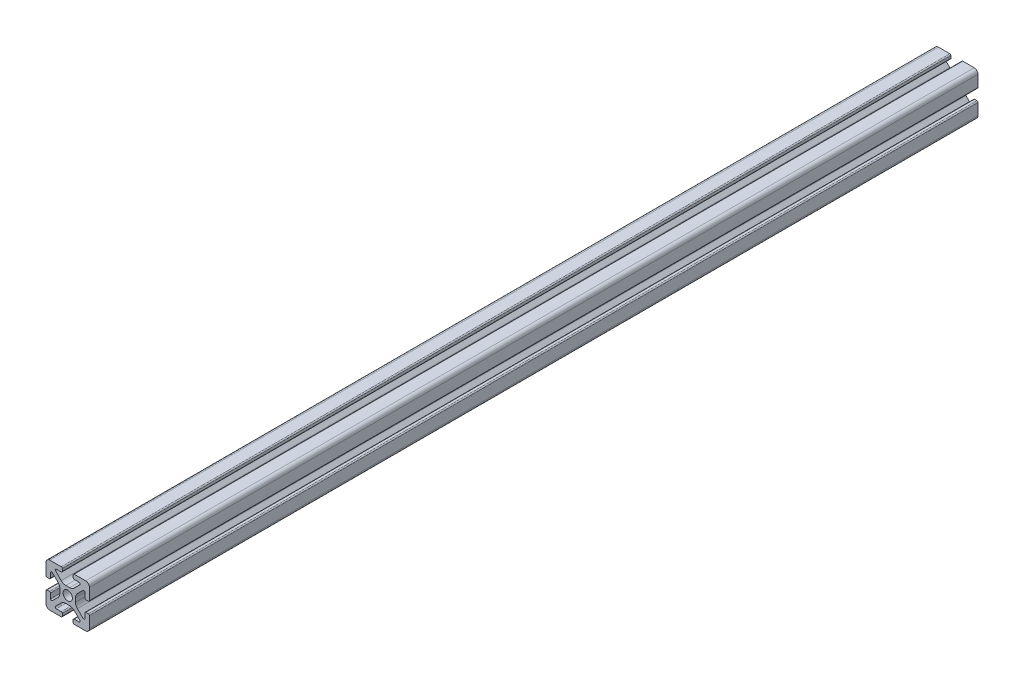
SolidWorks part; units mm, degrees
ref_plane "Front Plane" through (0, 0, 0) normal (0, 0, 1) x (1, 0, 0)
ref_plane "Top Plane" through (0, 0, 0) normal (0, 1, 0) x (1, 0, 0)
ref_plane "Right Plane" through (0, 0, 0) normal (1, 0, 0) x (0, 0, -1)
sketch "Sketch2" plane through (0, 0, 0) normal (0, 0, 1) x (1, 0, 0)
  line L0 (0, 10) -> (0, -10) construction
  line L1 (-10, 0) -> (10, 0) construction
  line L2 (2.5, -10) -> (10, -10)
  line L3 (10, -10) -> (10, -2.5)
  line L4 (2.5, -10) -> (2.5, -7.9246)
  line L5 (2.5, -7.9246) -> (6.4571, -7.9246)
  line L6 (6.4571, -7.9246) -> (2.1325, -3.6)
  line L7 (0, 0) -> (10, -10) construction
  line L8 (10, -2.5) -> (7.9246, -2.5)
  line L9 (7.9246, -2.5) -> (7.9246, -6.4571)
  line L10 (7.9246, -6.4571) -> (3.6, -2.1325)
  line L11 (5.7623, -4.2948) -> (4.2948, -5.7623) construction
  circle A0 centre (0, 0) radius 2.15
  arc A1 (5.25, -7.9246) -> (5.6036, -7.0711) centre (5.25, -7.4246) ccw construction
  point P8 (0, -3.6)
  point P16 (5.0286, -5.0286)
  dimension "Center Hole Diameter" = 4.3
  dimension "D3" = 0.5
  dimension "Rail Height" = 20
  dimension "Rail Width" = 20
  dimension "T-Slot Width" = 5
  dimension "Slot Depth" = 6.4
  dimension "Slot Inner Width" = 11.5
sketch "Sketch3" plane through (0, 0, 0) normal (1, 0, 0) x (0, 0, -1)
  line L0 (-304.8, -10) -> (304.8, -10) construction
  line L1 (-279.4, 0) -> (279.4, 0) construction
  line L2 (0, 10) -> (0, -10) construction
  line L3 (0, 10) -> (0, -10) construction
  point P6 (-279.4, 0)
  point P8 (279.4, 0)
  dimension "Length" = 609.6
  dimension "D1" = 25.4
sketch "Sketch4" plane through (0, 0, 0) normal (0, 0, 1) x (1, 0, 0)
  line L0 (3, -10) -> (8.25, -10)
  line L1 (2.5, -10) -> (10, -10) construction
  line L2 (2.5, -10) -> (2.5, -7.9246) construction
  line L3 (2.5, -7.9246) -> (6.4571, -7.9246) construction
  line L4 (2.5, -8.4246) -> (2.5, -9.5)
  line L5 (3, -7.9246) -> (5.25, -7.9246)
  line L6 (0, -3.6) -> (0.8898, -3.6)
  line L7 (6.4571, -7.9246) -> (2.1325, -3.6) construction
  line L8 (3.0112, -4.4787) -> (5.6036, -7.0711)
  line L9 (10, -10) -> (10, -2.5) construction
  line L10 (7.9246, -6.4571) -> (3.6, -2.1325) construction
  line L11 (7.9246, -2.5) -> (7.9246, -6.4571) construction
  line L12 (7.9246, -5.25) -> (7.9246, -3)
  line L13 (10, -2.5) -> (7.9246, -2.5) construction
  line L14 (8.4246, -2.5) -> (9.5, -2.5)
  line L15 (10, -3) -> (10, -8.25)
  line L16 (7.0711, -5.6036) -> (4.4787, -3.0112)
  line L17 (3.6, 0) -> (3.6, -0.8898)
  line L18 (-10, 0) -> (10, 0) construction
  line L19 (0, -3.6) -> (0, -2.15)
  line L20 (0, 10) -> (0, -10) construction
  line L21 (3.6, 0) -> (2.15, 0)
  arc A0 (2.5, -9.5) -> (3, -10) centre (3, -9.5) ccw
  arc A1 (5.25, -7.9246) -> (5.6036, -7.0711) centre (5.25, -7.4246) ccw construction
  arc A2 (2.5, -8.4246) -> (3, -7.9246) centre (3, -8.4246) cw
  arc A3 (5.25, -7.9246) -> (5.6036, -7.0711) centre (5.25, -7.4246) ccw
  arc A4 (0.8898, -3.6) -> (3.0112, -4.4787) centre (0.8898, -6.6) cw
  arc A5 (8.25, -10) -> (10, -8.25) centre (8.25, -8.25) ccw
  arc A6 (7.0711, -5.6036) -> (7.9246, -5.25) centre (7.4246, -5.25) ccw
  arc A7 (7.9246, -3) -> (8.4246, -2.5) centre (8.4246, -3) cw
  arc A8 (9.5, -2.5) -> (10, -3) centre (9.5, -3) cw
  arc A9 (4.4787, -3.0112) -> (3.6, -0.8898) centre (6.6, -0.8898) cw
  circle A10 centre (0, 0) radius 2.15 construction
  arc A11 (0, -2.15) -> (2.15, 0) centre (0, 0) ccw
  dimension "D1" = 1.75
  dimension "D2" = 3
extrude "Boss-Extrude1" add sketch "Sketch4" along normal mid plane 609.6
mirror "Mirror1" about plane through (0, 0, 0) normal (1, 0, 0) of bodies 134
mirror "Mirror2" about plane through (0, 0, 0) normal (0, 1, 0) of bodies 135
sketch "Sketch5" plane through (0, 0, -304.8) normal (0, 0, -1) x (-1, 0, 0)
  line L1 (-13.8311, 12.3183) -> (13.1641, 12.3183)
  line L2 (-13.8311, 12.3183) -> (-13.8311, -12.3688)
  line L3 (-13.8311, -12.3688) -> (13.1641, -12.3688)
  line L4 (13.1641, 12.3183) -> (13.1641, -12.3688)
extrude "Cut-Extrude1" cut sketch "Sketch5" against normal blind 200.025
equation "\"D3@Sketch2\"=\"T-Slot Width@Sketch2\"*0.1"
equation "\"D1@Sketch4\"=\"D3@Sketch2\"*3.5"
equation "\"D2@Sketch4\"=\"D3@Sketch2\"*6"
equation "\"D1@Boss-Extrude1\"=\"Length@Sketch3\""
